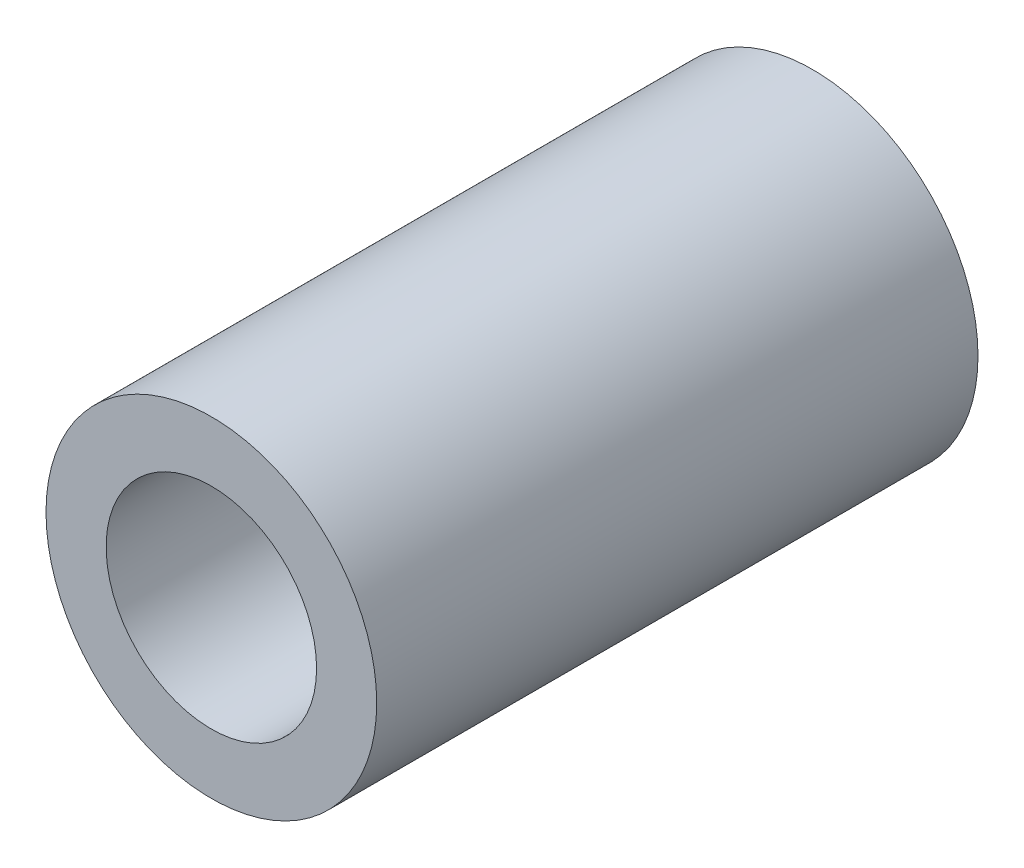
SolidWorks part; units mm, degrees
ref_plane "Ön Düzlem" through (0, 0, 0) normal (0, 0, 1) x (1, 0, 0)
ref_plane "Üst Düzlem" through (0, 0, 0) normal (0, 1, 0) x (1, 0, 0)
ref_plane "Sağ Düzlem" through (0, 0, 0) normal (1, 0, 0) x (0, 0, -1)
sketch "Sketch1" plane through (0, 0, 0) normal (0, 0, 1) x (1, 0, 0)
  circle A0 centre (0, 0) radius 2.5
  circle A1 centre (0, 0) radius 5.5
  dimension "D1" = 5
  dimension "D2" = 3
extrude "Boss-Extrude1" add sketch "Sketch1" along normal blind 20
sketch "Sketch2" plane through (0, 0, 20) normal (0, 0, 1) x (1, 0, 0)
  circle A0 centre (0, 0) radius 2.5
  circle A1 centre (0, 0) radius 2.5 construction
extrude "Boss-Extrude2" add sketch "Sketch2" against normal blind 2 from offset 15 offset against normal yes
sketch "Sketch3" plane through (0, 0, 5) normal (0, 0, 1) x (1, 0, 0)
  circle A0 centre (0, 0) radius 1
  dimension "D1" = 2
extrude "Cut-Extrude1" cut sketch "Sketch3" against normal blind 2
sketch "Sketch4" plane through (0, 0, 20) normal (0, 0, 1) x (1, 0, 0)
  circle A0 centre (0, 0) radius 3.5
  dimension "D1" = 7
extrude "Cut-Extrude3" cut sketch "Sketch4" against normal up to surface (15 mm away) up to face at (1, 0, 5)
